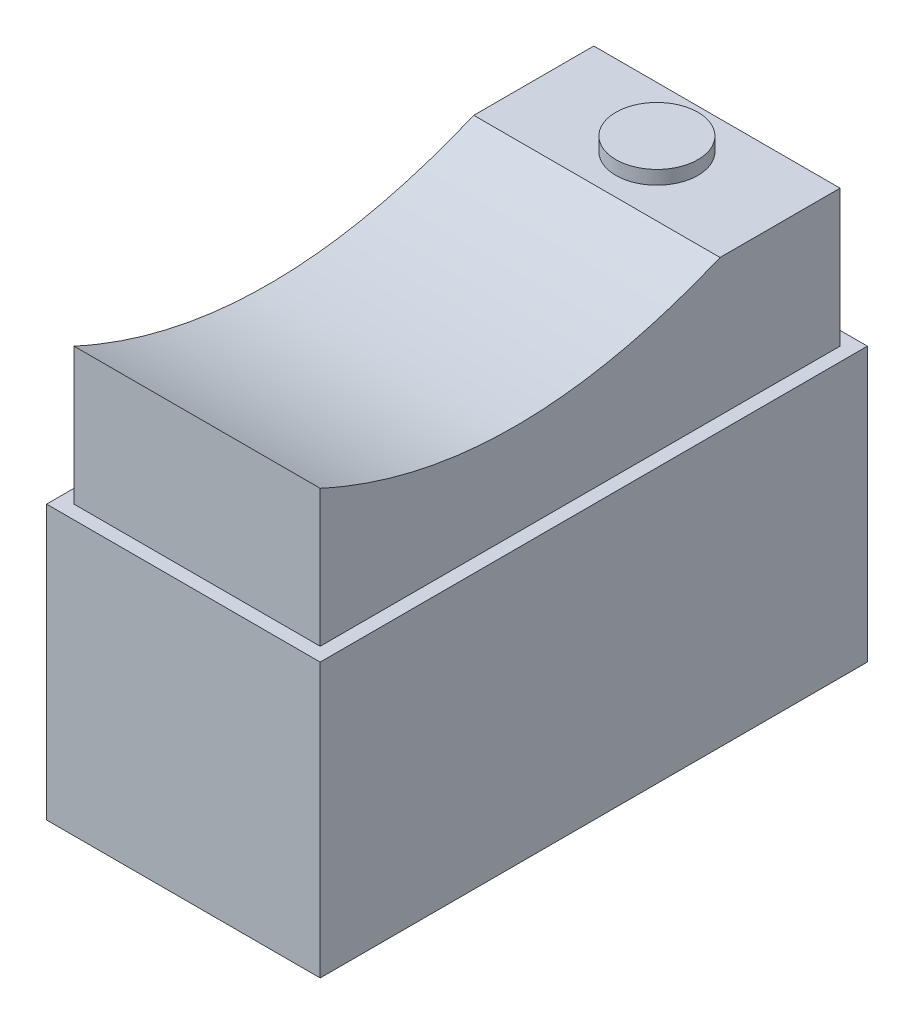
SolidWorks part; units mm, degrees
ref_plane "Alzado" through (0, 0, 0) normal (0, 0, 1) x (1, 0, 0)
ref_plane "Planta" through (0, 0, 0) normal (0, 1, 0) x (1, 0, 0)
ref_plane "Vista lateral" through (0, 0, 0) normal (1, 0, 0) x (0, 0, -1)
sketch "Croquis1" plane through (0, 0, 0) normal (0, 1, 0) x (1, 0, 0)
  line L1 (-10, -20) -> (10, -20)
  line L2 (-10, -20) -> (-10, 20)
  line L3 (-10, 20) -> (10, 20)
  line L4 (10, -20) -> (10, 20)
  line L5 (-10, -20) -> (10, 20) construction
  line L6 (-10, 20) -> (10, -20) construction
  point P0 (0, 0)
  dimension "D1" = 20
  dimension "D2" = 40
extrude "Saliente-Extruir1" add sketch "Croquis1" along normal blind 30
sketch "Croquis2" plane through (0, 30, 0) normal (0, 1, 0) x (1, 0, 0)
  line L1 (-9, -19) -> (9, -19)
  line L2 (-9, -19) -> (-9, 19)
  line L3 (-9, 19) -> (9, 19)
  line L4 (9, -19) -> (9, 19)
  line L5 (-9, -19) -> (9, 19) construction
  line L6 (-9, 19) -> (9, -19) construction
  line L7 (-10, -20) -> (10, -20)
  line L8 (-10, -20) -> (-10, 20)
  line L9 (-10, 20) -> (10, 20)
  line L10 (10, -20) -> (10, 20)
  line L11 (-10, -20) -> (10, 20) construction
  line L12 (-10, 20) -> (10, -20) construction
  point P0 (0, 0)
  point P6 (0, 0)
  dimension "D1" = 18
  dimension "D2" = 38
  dimension "D3" = 40
  dimension "D4" = 20
extrude "Cortar-Extruir1" cut sketch "Croquis2" against normal blind 10
sketch "Croquis3" plane through (-9, 0, 0) normal (-1, 0, 0) x (0, 0, 1)
  line L0 (-19, 30) -> (19, 30) construction
  spline S0 degree 2 poles (-10.2264, 30) (5.1114, 23.5924) (19, 30) knots 0 0 0 1 1 1
extrude "Cortar-Extruir2" cut sketch "Croquis3" against normal through all and the other way through all
sketch "Croquis4" plane through (0, 30, 0) normal (0, 1, 0) x (1, 0, 0)
  circle A0 centre (0, 14.6132) radius 3
  dimension "D1" = 6
extrude "Saliente-Extruir2" add sketch "Croquis4" along normal blind 1
